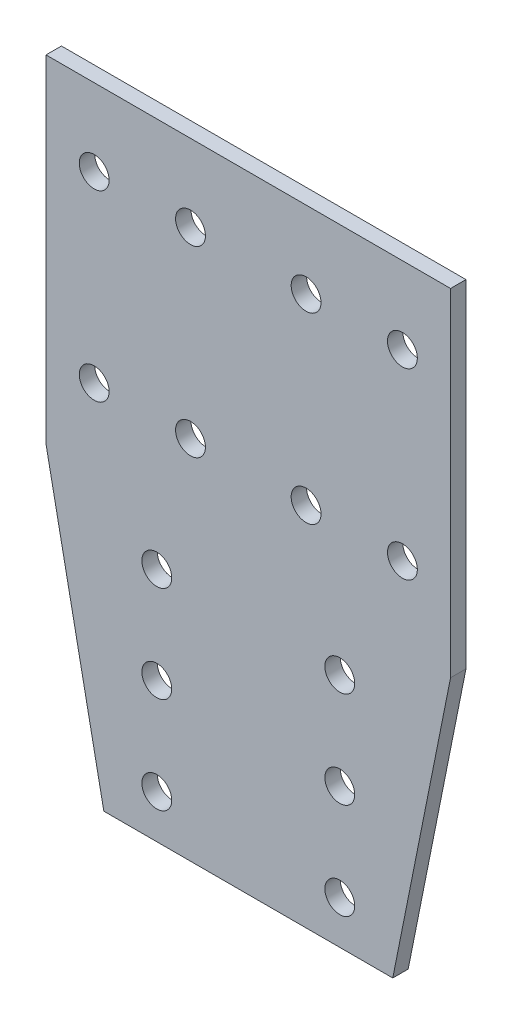
SolidWorks part; units mm, degrees
ref_plane "前视基准面" through (0, 0, 0) normal (0, 0, 1) x (1, 0, 0)
ref_plane "上视基准面" through (0, 0, 0) normal (0, 1, 0) x (1, 0, 0)
ref_plane "右视基准面" through (0, 0, 0) normal (1, 0, 0) x (0, 0, -1)
sketch "草图1" plane through (0, 0, 0) normal (0, 0, 1) x (1, 0, 0)
  line L0 (-1117.9557, 0) -> (48882.0443, 0) construction
  line L1 (170.7801, -702.6879) -> (170.7801, 49297.3121) construction
  line L2 (380.7801, 350) -> (-39.2199, 350)
  line L3 (-39.2199, 350) -> (-39.2199, 0)
  line L4 (-39.2199, 0) -> (20.7801, -300)
  line L5 (20.7801, -300) -> (320.7801, -300)
  line L6 (380.7801, 0) -> (320.7801, -300)
  line L7 (380.7801, 350) -> (380.7801, 0)
  line L8 (-1585.653, 175) -> (48414.347, 175) construction
  circle A0 centre (75.7801, -255) radius 15.5
  circle A1 centre (75.7801, -55) radius 15.5
  circle A2 centre (75.7801, -155) radius 15.5
  circle A3 centre (110.7801, 80) radius 15.5
  circle A4 centre (10.7801, 80) radius 15.5
  circle A5 centre (110.7801, 270) radius 15.5
  circle A6 centre (10.7801, 270) radius 15.5
  circle A7 centre (330.7801, 270) radius 15.5
  circle A8 centre (230.7801, 270) radius 15.5
  circle A9 centre (330.7801, 80) radius 15.5
  circle A10 centre (230.7801, 80) radius 15.5
  circle A11 centre (265.7801, -155) radius 15.5
  circle A12 centre (265.7801, -55) radius 15.5
  circle A13 centre (265.7801, -255) radius 15.5
  point P11 (170.7801, -300)
  point P13 (170.7801, 350)
  dimension "D1" = 31
  dimension "D6" = 31
  dimension "D8" = 31
  dimension "D10" = 31
  dimension "D13" = 31
  dimension "D2" = 45
  dimension "D3" = 150
  dimension "D4" = 300
  dimension "D5" = 95
  dimension "D7" = 200
  dimension "D9" = 100
  dimension "D11" = 60
  dimension "D12" = 135
  dimension "D14" = 100
  dimension "D15" = 175
extrude "拉伸1" add sketch "草图1" along normal blind 16
